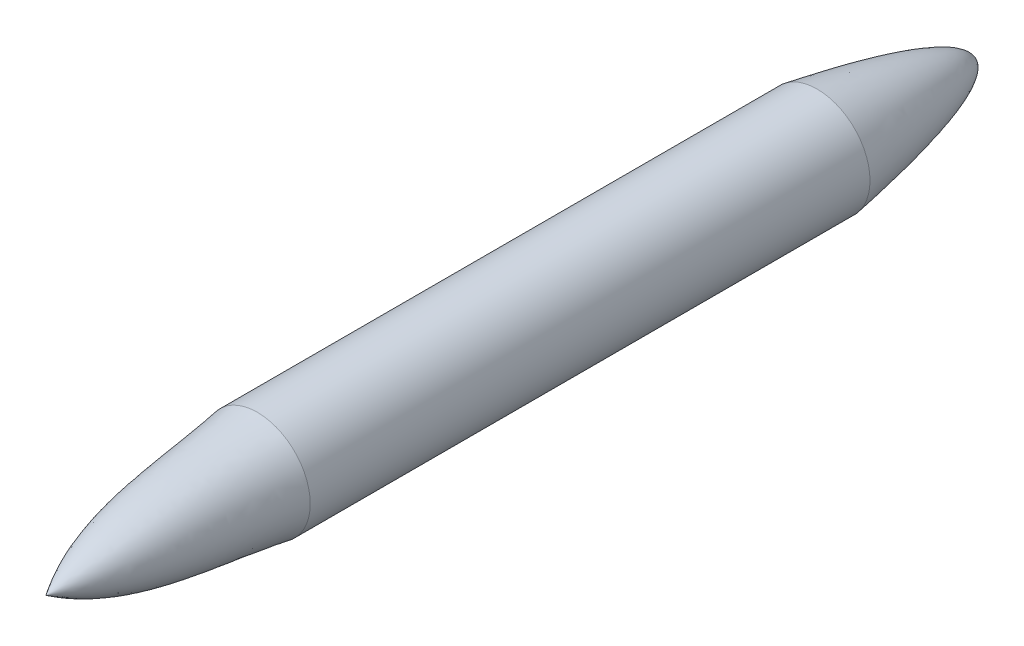
SolidWorks part; units mm, degrees
ref_plane "Front Plane" through (0, 0, 0) normal (0, 0, 1) x (1, 0, 0)
ref_plane "Top Plane" through (0, 0, 0) normal (0, 1, 0) x (1, 0, 0)
ref_plane "Right Plane" through (0, 0, 0) normal (1, 0, 0) x (0, 0, -1)
sketch "Base" plane through (0, 0, 0) normal (0, 1, 0) x (1, 0, 0)
  line L0 (0, -17495.52) -> (0, 17495.52) construction
  line L2 (-1993.392, 11595.0797) -> (-1993.392, -9521.952)
  line L4 (1993.392, 11595.0797) -> (1993.392, -9521.952) construction
  line L7 (0, -17495.52) -> (0, 17495.52)
  line L8 (21040.1302, -22682.3259) -> (21040.1302, -22284.3259) construction
  line L23 (0, -9521.952) -> (0, -17495.52) construction
  line L24 (0, 17495.52) -> (0, 47975.52) construction
  line L31 (-19232.818, -22851.5097) -> (-18899.4847, -22851.5097) construction
  arc A0 (1993.392, -7528.56) -> (-1993.392, -7528.56) centre (0, -7528.56) cw construction
  spline S0 degree 2 poles (-1993.392, 11595.0797) (-996.696, 17495.52) (0, 17495.52) knots 0 0 0 0.5 0.5 0.5
  spline S1 degree 3 poles (-1993.392, -9521.952) (-1540.99, -12218.2816) (-1564.1113, -15114.5071) (0, -17495.52) knots 0 0 0 0 1 1 1 1
  point P6 (0, 11595.0797)
  point P10 (0, -9521.952)
  point P11 (0, -7528.56)
  point P12 (1993.392, -7528.56)
  point P13 (-1993.392, -7528.56)
  point P18 (1993.392, 11595.0797)
  point P29 (-1993.392, 11595.0797)
  point P61 (-1993.392, -9521.952)
  dimension "D7" = 1993.392
  dimension "D3" = 5900.4403
  dimension "D4" = 7973.568
  dimension "D5" = 1993.392
  dimension "D27" = 30480
revolve "Revolve3" add sketch "Base" angle 360 about L24
equation "\"Diameter\"= 13.08'Input"
equation "\"Length\"= 164 * 0.7'Input, usually 60%-80%"
equation "\"L/D Nose Shape\"= 1.48'Fig. 5-17"
equation "\"L/D Afterbody Shape\"= 2'Fig. 5-19"
equation "\"Length Nose\"= \"L/D Nose Shape\" * \"Diameter\""
equation "\"Length Afterbody\"= \"L/D Afterbody Shape\" * \"Diameter\""
equation "\"D3@Base\" = \"Length Nose\""
equation "\"D4@Base\" = \"Length Afterbody\""
equation "\"D5@Base\" = \"Diameter\" * 0.5"
equation "\"0.25 MAC / Length\"= 0.46'Fig. 5-22"
equation "\"0.25 MAX x\"= \"0.25 MAC / Length\" * \"Length\""
equation "\"D7@Base\" = \"Diameter\" * 0.5"
equation "\"Root Chord W\"= 2 * \"S_ref\" / ( \"Span W\" * ( 1 + \"Taper Ratio W\" ) )"
equation "\"Tip Chord W\"= \"Root Chord W\" * \"Taper Ratio W\""
equation "\"Swept Angle W\"= 30'Input"
equation "\"Span W\"= sqr ( \"S_ref\" * \"AR W\" )"
equation "\"AR W\"= 8'Input"
equation "\"S_ref\"= 1929.58677544867'Input"
equation "\"Taper Ratio W\"= 0.35'Input"
equation "\"MAC W\"= ( 2 / 3 ) * \"Root Chord W\" * ( 1 + \"Taper Ratio W\" - ( \"Taper Ratio W\" / ( 1 + \"Taper Ratio W\" ) ) )"
equation "\"Y W\"= ( \"Span W\" / 6 ) * ( ( 1 + 2 * \"Taper Ratio W\" ) / ( 1 + \"Taper Ratio W\" ) )"
equation "\"Root Chord H\"= 2 * \"S H\" / ( \"Span H\" * ( 1 + \"Taper Ratio H\" ) )"
equation "\"Tip Chord H\"= \"Root Chord H\" * \"Taper Ratio H\""
equation "\"Swept Angle H\"= \"Swept Angle W\" + 5"
equation "\"Span H\"= sqr ( \"S H\" * \"AR H\" )"
equation "\"AR H\"= 4'Figure 6-17"
equation "\"Taper Ratio H\"= 0.35'Figure 6-17"
equation "\"V H\"= 0.34144516'Input"
equation "\"S H\"= \"V H\" * 1929.586775 * 17.885852 / \"l H\"'Equation 6-3"
equation "\"MAC H\"= ( 2 / 3 ) * \"Root Chord H\" * ( 1 + \"Taper Ratio H\" - \"Taper Ratio H\" / ( 1 + \"Taper Ratio H\" ) )'Equation 4-19"
equation "\"Y H\"= ( \"Span H\" / 6 ) * ( 1 + 2 * \"Taper Ratio H\" ) / ( 1 + \"Taper Ratio H\" )'Equation 4-20"
equation "\"l H\"= \"Span W\" * 0.4'40% span"
